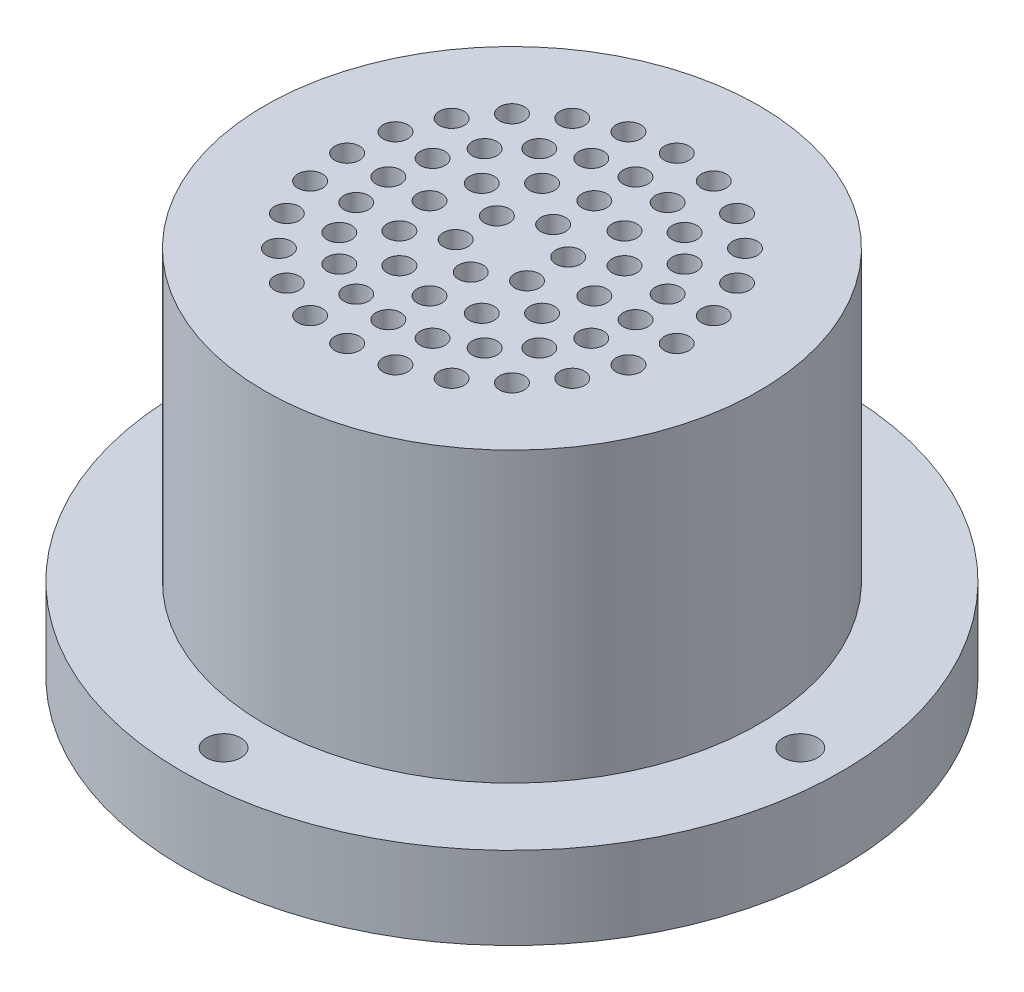
SolidWorks part; units mm, degrees
ref_plane "Front Plane" through (0, 0, 0) normal (0, 0, 1) x (1, 0, 0)
ref_plane "Top Plane" through (0, 0, 0) normal (0, 1, 0) x (1, 0, 0)
ref_plane "Right Plane" through (0, 0, 0) normal (1, 0, 0) x (0, 0, -1)
sketch "Sketch2" plane through (0, 0, 0) normal (0, 1, 0) x (1, 0, 0)
  circle A0 centre (0, 0) radius 40
  circle A1 centre (0, 0) radius 25
  circle A2 centre (35, 0) radius 2.1
  circle A3 centre (0, -35) radius 2.1
  circle A4 centre (-35, 0) radius 2.1
  circle A5 centre (0, 35) radius 2.1
  point P15 (0, 0)
  dimension "D1" = 80
  dimension "D2" = 50
  dimension "D3" = 35
  dimension "D4" = 4.2
  dimension "D5" = 4
extrude "Boss-Extrude1" add sketch "Sketch2" along normal blind 10
sketch "Sketch4" plane through (0, 10, 0) normal (0, 1, 0) x (1, 0, 0)
  circle A0 centre (0, 0) radius 25
  circle A1 centre (0, 0) radius 30
  dimension "D1" = 50
  dimension "D2" = 60
extrude "Boss-Extrude2" add sketch "Sketch4" along normal blind 30
sketch "Sketch5" plane through (0, 40, 0) normal (0, 1, 0) x (1, 0, 0)
  circle A0 centre (0, 0) radius 30
  circle A1 centre (0, 5) radius 1.5
  circle A2 centre (0, 10) radius 1.5
  circle A3 centre (0, 15) radius 1.5
  circle A4 centre (0, 20) radius 1.5
  circle A5 centre (4.3301, 2.5) radius 1.5
  circle A6 centre (4.3301, -2.5) radius 1.5
  circle A7 centre (0, -5) radius 1.5
  circle A8 centre (-4.3301, -2.5) radius 1.5
  circle A9 centre (-4.3301, 2.5) radius 1.5
  circle A10 centre (5, 8.6603) radius 1.5
  circle A11 centre (8.6603, 5) radius 1.5
  circle A12 centre (10, 0) radius 1.5
  circle A13 centre (8.6603, -5) radius 1.5
  circle A14 centre (5, -8.6603) radius 1.5
  circle A15 centre (0, -10) radius 1.5
  circle A16 centre (-5, -8.6603) radius 1.5
  circle A17 centre (-8.6603, -5) radius 1.5
  circle A18 centre (-10, 0) radius 1.5
  circle A19 centre (-8.6603, 5) radius 1.5
  circle A20 centre (-5, 8.6603) radius 1.5
  circle A21 centre (4.6353, 14.2658) radius 1.5
  circle A22 centre (8.8168, 12.1353) radius 1.5
  circle A23 centre (12.1353, 8.8168) radius 1.5
  circle A24 centre (14.2658, 4.6353) radius 1.5
  circle A25 centre (15, 0) radius 1.5
  circle A26 centre (14.2658, -4.6353) radius 1.5
  circle A27 centre (12.1353, -8.8168) radius 1.5
  circle A28 centre (8.8168, -12.1353) radius 1.5
  circle A29 centre (4.6353, -14.2658) radius 1.5
  circle A30 centre (0, -15) radius 1.5
  circle A31 centre (-4.6353, -14.2658) radius 1.5
  circle A32 centre (-8.8168, -12.1353) radius 1.5
  circle A33 centre (-12.1353, -8.8168) radius 1.5
  circle A34 centre (-14.2658, -4.6353) radius 1.5
  circle A35 centre (-15, 0) radius 1.5
  circle A36 centre (-14.2658, 4.6353) radius 1.5
  circle A37 centre (-12.1353, 8.8168) radius 1.5
  circle A38 centre (-8.8168, 12.1353) radius 1.5
  circle A39 centre (-4.6353, 14.2658) radius 1.5
  circle A40 centre (5.1764, 19.3185) radius 1.5
  circle A41 centre (10, 17.3205) radius 1.5
  circle A42 centre (14.1421, 14.1421) radius 1.5
  circle A43 centre (17.3205, 10) radius 1.5
  circle A44 centre (19.3185, 5.1764) radius 1.5
  circle A45 centre (20, 0) radius 1.5
  circle A46 centre (19.3185, -5.1764) radius 1.5
  circle A47 centre (17.3205, -10) radius 1.5
  circle A48 centre (14.1421, -14.1421) radius 1.5
  circle A49 centre (10, -17.3205) radius 1.5
  circle A50 centre (5.1764, -19.3185) radius 1.5
  circle A51 centre (0, -20) radius 1.5
  circle A52 centre (-5.1764, -19.3185) radius 1.5
  circle A53 centre (-10, -17.3205) radius 1.5
  circle A54 centre (-14.1421, -14.1421) radius 1.5
  circle A55 centre (-17.3205, -10) radius 1.5
  circle A56 centre (-19.3185, -5.1764) radius 1.5
  circle A57 centre (-20, 0) radius 1.5
  circle A58 centre (-19.3185, 5.1764) radius 1.5
  circle A59 centre (-17.3205, 10) radius 1.5
  circle A60 centre (-14.1421, 14.1421) radius 1.5
  circle A61 centre (-10, 17.3205) radius 1.5
  circle A62 centre (-5.1764, 19.3185) radius 1.5
  point P23 (0, 0)
  point P46 (0, 0)
  point P85 (0, 0)
  point P132 (0, 0)
  dimension "D1" = 60
  dimension "D2" = 3
  dimension "D3" = 5
  dimension "D4" = 4
  dimension "D5" = 6
  dimension "D6" = 12
  dimension "D7" = 20
  dimension "D8" = 24
extrude "Boss-Extrude3" add sketch "Sketch5" along normal blind 5
